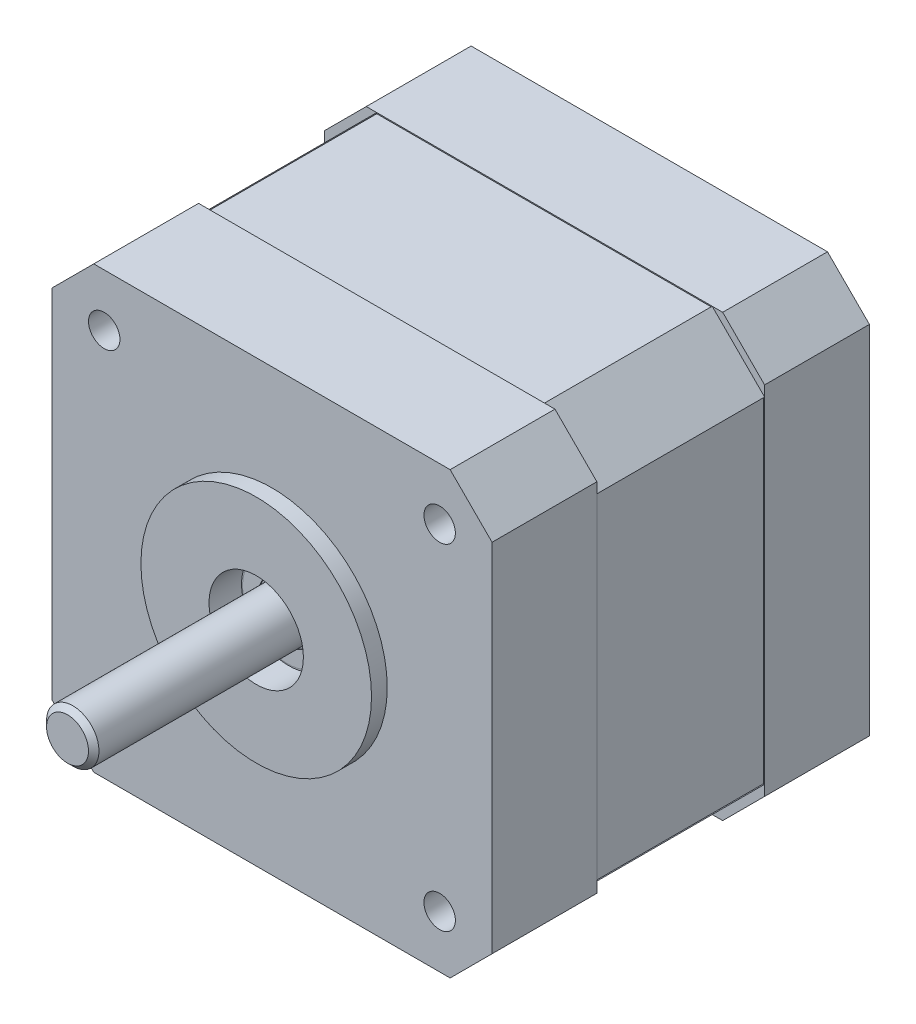
SolidWorks part; units mm, degrees
ref_plane "前视基准面" through (0, 0, 0) normal (0, 0, 1) x (1, 0, 0)
ref_plane "上视基准面" through (0, 0, 0) normal (0, 1, 0) x (1, 0, 0)
ref_plane "右视基准面" through (0, 0, 0) normal (1, 0, 0) x (0, 0, -1)
sketch "草图1" plane through (0, 0, 0) normal (0, 0, 1) x (1, 0, 0)
  line L0 (0, 44.76) -> (0, -44.76) construction
  line L1 (-38.76, 0) -> (72.6, 0) construction
  line L2 (-21, 17) -> (-17, 21)
  line L3 (-17, 21) -> (17, 21)
  line L4 (-21, 17) -> (-21, -17)
  line L5 (-17, -21) -> (17, -21)
  line L6 (21, 17) -> (21, -17)
  line L7 (17, 21) -> (21, 17)
  line L8 (17, -21) -> (21, -17)
  line L9 (-21, -17) -> (-17, -21)
  circle A0 centre (0, 0) radius 4.5
  circle A1 centre (-16, 16) radius 3
  circle A2 centre (16, 16) radius 3
  circle A3 centre (16, -16) radius 3
  circle A4 centre (-16, -16) radius 3
  point P5 (-21, 21)
  point P6 (21, -21)
  point P7 (-21, -21)
  point P8 (21, 21)
  dimension "D5" = 9
  dimension "D6" = 6
  dimension "D11" = 5
  dimension "D12" = 5
  dimension "D1" = 42
  dimension "D2" = 42
  dimension "D3" = 21
  dimension "D4" = 21
extrude "凸台-拉伸1" add sketch "草图1" along normal blind 10
sketch "草图2" plane through (0, 0, 10) normal (0, 0, 1) x (1, 0, 0)
  line L0 (0, -21) -> (0, 21) construction
  line L1 (17, 21) -> (-17, 21) construction
  line L2 (21, 0) -> (-21, 0) construction
  line L3 (-21, 17) -> (-21, -17) construction
  line L4 (16, 21) -> (-16, 21)
  line L5 (-21, 16) -> (-21, -16)
  line L7 (16, 21) -> (21, 16)
  line L9 (21, 16) -> (21, -16)
  line L10 (-16, 21) -> (-21, 16)
  line L12 (-16, -21) -> (-21, -16)
  line L13 (16, -21) -> (21, -16)
  line L14 (16, -21) -> (-16, -21)
  point P14 (0, 0)
  dimension "D1" = 45
  dimension "D2" = 1
extrude "凸台-拉伸2" add sketch "草图2" along normal blind 16
sketch "草图3" plane through (0, 0, 26) normal (0, 0, 1) x (1, 0, 0)
  line L0 (-17, 21) -> (-21, 17) construction
  line L1 (-17, 21) -> (-21, 17)
  line L2 (21, 17) -> (17, 21) construction
  line L3 (16, 21) -> (-16, 21) construction
  line L4 (21, -16) -> (21, 16) construction
  line L5 (-21, 16) -> (-21, -16) construction
  line L6 (-16, -21) -> (16, -21) construction
  line L7 (-21, -17) -> (-17, -21) construction
  line L8 (17, -21) -> (21, -17) construction
  line L9 (-17, -21) -> (-16, -21) construction
  line L10 (-21, -16) -> (-21, -17) construction
  line L11 (21, -17) -> (21, -16) construction
  line L12 (16, -21) -> (17, -21) construction
  line L13 (21, 16) -> (21, 17) construction
  line L14 (17, 21) -> (16, 21) construction
  line L15 (-16, 21) -> (-17, 21) construction
  line L16 (-21, 17) -> (-21, 16) construction
  line L17 (21, 17) -> (17, 21)
  line L18 (16, 21) -> (-16, 21)
  line L19 (21, -16) -> (21, 16)
  line L20 (-21, 16) -> (-21, -16)
  line L21 (-16, -21) -> (16, -21)
  line L22 (-21, -17) -> (-17, -21)
  line L23 (17, -21) -> (21, -17)
  line L24 (-17, -21) -> (-16, -21)
  line L25 (-21, -16) -> (-21, -17)
  line L26 (21, -17) -> (21, -16)
  line L27 (16, -21) -> (17, -21)
  line L28 (21, 16) -> (21, 17)
  line L29 (17, 21) -> (16, 21)
  line L30 (-16, 21) -> (-17, 21)
  line L31 (-21, 17) -> (-21, 16)
  line L32 (0, 0) -> (-21, 0) construction
  line L33 (-21, 0) -> (0, 0) construction
  line L34 (0, 0) -> (0, 21) construction
  circle A0 centre (-16, 16) radius 1.5
  circle A1 centre (16, 16) radius 1.5
  circle A2 centre (16, -16) radius 1.5
  circle A3 centre (-16, -16) radius 1.5
  dimension "D1" = 3
  dimension "D2" = 5
  dimension "D3" = 5
extrude "凸台-拉伸3" add sketch "草图3" along normal blind 10
sketch "草图5" plane through (-21, 0, 0) normal (-1, 0, 0) x (0, 0, 1)
  line L0 (26, 16) -> (26, -16)
  line L1 (26, -16) -> (10, -16)
  line L2 (10, -16) -> (10, 16)
  line L3 (10, 16) -> (26, 16)
extrude "切除-拉伸1" cut sketch "草图5" against normal blind 0.1
sketch "草图6" plane through (0, 21, 0) normal (0, 1, 0) x (1, 0, 0)
  line L0 (16, -26) -> (-16, -26)
  line L1 (-16, -26) -> (-16, -10)
  line L2 (-16, -10) -> (16, -10)
  line L3 (16, -10) -> (16, -26)
extrude "切除-拉伸2" cut sketch "草图6" against normal blind 0.1
sketch "草图7" plane through (21, 0, 0) normal (1, 0, 0) x (0, 0, -1)
  line L0 (-10, -16) -> (-10, 16)
  line L1 (-10, 16) -> (-26, 16)
  line L2 (-26, 16) -> (-26, -16)
  line L3 (-26, -16) -> (-10, -16)
extrude "切除-拉伸3" cut sketch "草图7" against normal blind 0.1
sketch "草图8" plane through (0, -21, 0) normal (0, -1, 0) x (1, 0, 0)
  line L0 (-16, 26) -> (16, 26)
  line L1 (16, 26) -> (16, 10)
  line L2 (16, 10) -> (-16, 10)
  line L3 (-16, 10) -> (-16, 26)
extrude "切除-拉伸4" cut sketch "草图8" against normal blind 0.1
sketch "草图9" plane through (0, 0, 26) normal (0, 0, 1) x (1, 0, 0)
  circle A1 centre (-16, 16) radius 1.5 construction
  circle A2 centre (-16, -16) radius 1.5
  circle A3 centre (-16, -16) radius 1.5
  circle A4 centre (16, 16) radius 1.5 construction
  circle A5 centre (16, -16) radius 1.5 construction
  circle A6 centre (-16, 16) radius 1.5
  circle A7 centre (16, 16) radius 1.5
  circle A8 centre (16, -16) radius 1.5
  dimension "D1" = 0
extrude "切除-拉伸5" cut sketch "草图9" against normal through all
sketch "草图10" plane through (0, 0, 36) normal (0, 0, 1) x (1, 0, 0)
  circle A0 centre (0, 0) radius 11
  dimension "D1" = 22
extrude "凸台-拉伸4" add sketch "草图10" along normal blind 1.5
sketch "草图11" plane through (0, 0, 37.5) normal (0, 0, 1) x (1, 0, 0)
  circle A0 centre (0, 0) radius 4.5
  dimension "D1" = 9
extrude "切除-拉伸6" cut sketch "草图11" against normal blind 3
sketch "草图12" plane through (0, 0, 10) normal (0, 0, -1) x (-1, 0, 0)
  circle A0 centre (0, 0) radius 4
  dimension "D1" = 8
extrude "凸台-拉伸5" add sketch "草图12" along normal blind 9
chamfer "倒角1" distance 1 angle 45 1 edges at (-4, 0, 1)
sketch "草图13" plane through (0, 0, 34.5) normal (0, 0, 1) x (1, 0, 0)
  circle A0 centre (0, 0) radius 2.5
  dimension "D1" = 5
extrude "凸台-拉伸6" add sketch "草图13" along normal blind 21
sketch "草图14" plane through (0, 0, 34.5) normal (0, 0, 1) x (1, 0, 0)
  circle A0 centre (0, 0) radius 2.8
  circle A1 centre (0, 0) radius 2.5 construction
  circle A2 centre (0, 0) radius 2.5
  dimension "D1" = 5.6
extrude "切除-拉伸7" cut sketch "草图14" against normal blind 0.1
sketch "草图15" plane through (0, 0, 34.5) normal (0, 0, 1) x (1, 0, 0)
  circle A0 centre (0, 0) radius 4.3
  circle A1 centre (0, 0) radius 4.5
  circle A2 centre (0, 0) radius 4.5
  dimension "D2" = 8.6
  dimension "D1" = 0
extrude "切除-拉伸8" cut sketch "草图15" against normal blind 0.1
chamfer "倒角2" distance 0.5 angle 45 1 edges at (2.5, 0, 55.5)
